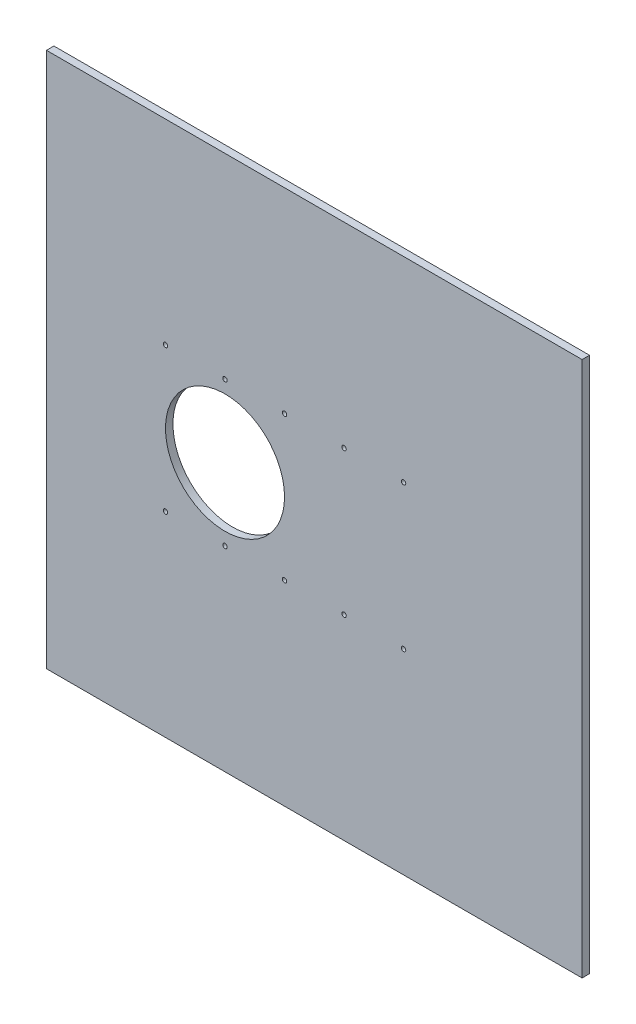
SolidWorks part; units mm, degrees
material "Pine"
ref_plane "Front Plane" through (0, 0, 0) normal (0, 0, 1) x (1, 0, 0)
ref_plane "Top Plane" through (0, 0, 0) normal (0, 1, 0) x (1, 0, 0)
ref_plane "Right Plane" through (0, 0, 0) normal (1, 0, 0) x (0, 0, -1)
sketch "Sketch1" plane through (0, 0, 0) normal (0, 0, 1) x (1, 0, 0)
  line L1 (0, 0) -> (457.2, 0)
  line L2 (0, 0) -> (0, 457.2)
  line L3 (0, 457.2) -> (457.2, 457.2)
  line L4 (457.2, 0) -> (457.2, 457.2)
  circle A0 centre (152.4, 228.6) radius 50.8
  dimension "D3" = 101.6
  dimension "D1" = 457.2
  dimension "D2" = 457.2
  dimension "D4" = 152.4
  dimension "D5" = 228.6
extrude "Boss-Extrude1" add sketch "Sketch1" along normal blind 6.35
hole_wizard "CSK for #6 Flat Head Machine Screw (100)1" positions "Sketch4" profile "Sketch5" countersink size "#6" standard "ANSI Inch" end condition through all
sketch "Sketch4" plane through (0, 0, 0) normal (0, 0, -1) x (-1, 0, 0)
  line L0 (-152.4, 228.6) -> (-152.4, 167.005)
  line L1 (-152.4, 167.005) -> (-101.6, 167.005)
  line L2 (-101.6, 167.005) -> (-101.6, 290.195)
  line L3 (-101.6, 290.195) -> (-152.4, 290.195)
  line L4 (-152.4, 290.195) -> (-152.4, 228.6)
  line L6 (-152.4, 290.195) -> (-203.2, 290.195)
  line L7 (-203.2, 290.195) -> (-203.2, 167.005)
  line L8 (-203.2, 167.005) -> (-152.4, 167.005)
  line L10 (-254, 290.195) -> (-203.2, 290.195)
  line L12 (-304.8, 290.195) -> (-254, 290.195)
  point P0 (-101.6, 290.195)
  point P2 (-152.4, 290.195)
  point P4 (-203.2, 290.195)
  point P6 (-203.2, 167.005)
  point P8 (-152.4, 167.005)
  point P10 (-101.6, 167.005)
  point P29 (-254, 290.195)
  point P31 (-304.8, 290.195)
  point P33 (-304.8, 167.005)
  point P35 (-254, 167.005)
  dimension "D1" = 50.8
  dimension "D2" = 123.19
sketch "Sketch5" plane through (101.6, 290.195, 0) normal (1, 0, 0) x (0, 1, 0)
  line L0 (0, 0) -> (0, 6.35)
  line L1 (0, 6.35) -> (1.8986, 6.35)
  line L2 (1.8986, 6.35) -> (1.8986, 1.38)
  line L3 (1.8986, 1.38) -> (3.5433, 0)
  line L5 (3.5433, 0) -> (0, 0)
  line L6 (-1.8986, 1.38) -> (-3.5433, 0) construction
  line L11 (0, -6.35) -> (0, 107.95) construction
  dimension "Thru Hole Dia." = 3.7973
  dimension "Thru Hole Depth" = 6.35
  dimension "Near C'Sink Dia." = 7.0866
  dimension "Near C'Sink Angle" = 100
